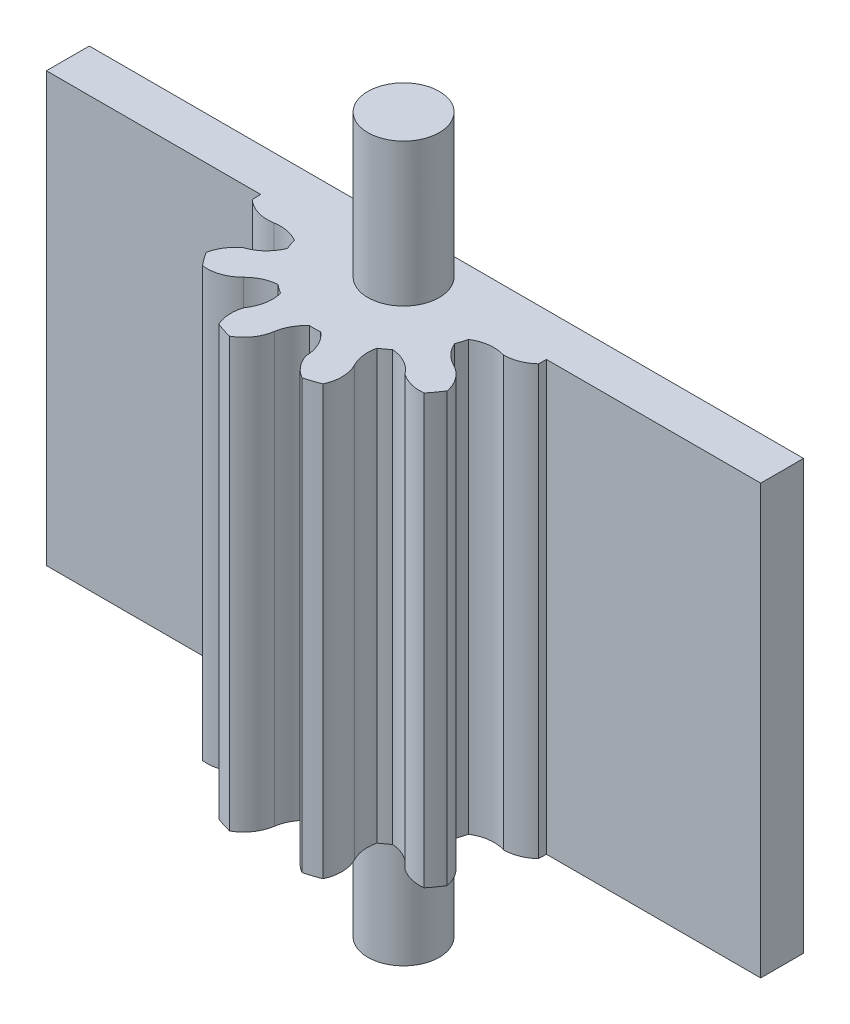
SolidWorks part; units mm, degrees
ref_plane "Alzado" through (0, 0, 0) normal (0, 0, 1) x (1, 0, 0)
ref_plane "Planta" through (0, 0, 0) normal (0, 1, 0) x (1, 0, 0)
ref_plane "Vista lateral" through (0, 0, 0) normal (1, 0, 0) x (0, 0, -1)
sketch "Croquis1" plane through (0, 0, 0) normal (0, 0, 1) x (1, 0, 0)
  line L1 (0, 0) -> (50, 0)
  line L2 (0, 0) -> (0, 30)
  line L3 (0, 30) -> (50, 30)
  line L4 (50, 0) -> (50, 30)
  dimension "D1" = 50
  dimension "D2" = 30
extrude "Saliente-Extruir1" add sketch "Croquis1" along normal blind 3
ref_plane "Plano1" through (0, 15, 0) normal (0, 1, 0) x (1, 0, 0)
sketch "Croquis2" plane through (0, 15, 0) normal (0, 1, 0) x (1, 0, 0)
  line L0 (50, -3) -> (0, -3) construction
  line L1 (15, -3) -> (35, -3)
  arc A0 (15, -3) -> (35, -3) centre (25, -3) ccw
  point P19 (0, 0)
  dimension "D1" = 20
extrude "Saliente-Extruir2" add sketch "Croquis2" along normal up to vertex (15 mm away) and the other way up to vertex (15 mm away)
sketch "Croquis3" plane through (0, 30, 0) normal (0, 1, 0) x (1, 0, 0)
  line L0 (25, -3) -> (18.9587, -4.6019) construction
  line L2 (25, -3) -> (21.0541, -7.847) construction
  arc A0 (17.281, -9.3575) -> (19.4133, -8.6169) centre (17.5958, -6.8239) ccw
  arc A2 (21.0541, -7.847) -> (19.4133, -8.6169) centre (21.2771, -10.4555) ccw
  arc A3 (21.0541, -7.847) -> (21.6882, -8.3005) centre (25, -3) ccw
  arc A6 (17.6058, -6.8433) -> (19.2052, -5.3416) centre (16.7783, -4.3595) ccw
  arc A8 (17.6058, -6.8433) -> (16.5983, -8.4232) centre (19.1632, -8.9478) ccw
  arc A9 (21.2771, -10.4555) -> (21.6882, -8.3005) centre (19.1476, -8.9325) ccw
  arc A10 (21.2771, -10.4555) -> (21.3905, -12.3259) centre (23.774, -11.2427) ccw
  arc A11 (18.9587, -4.6019) -> (17.1787, -4.2604) centre (17.6058, -6.8433) ccw
  arc A12 (18.9587, -4.6019) -> (19.2052, -5.3416) centre (25, -3) ccw
  arc A13 (15.0184, -3.6062) -> (17.1787, -4.2604) centre (16.7622, -1.7415) ccw
  arc A14 (16.5983, -8.4232) -> (15.0184, -3.6062) centre (25, -3) cw
  arc A15 (21.3905, -12.3259) -> (17.281, -9.3575) centre (25, -3) cw
  arc A16 (22.4921, -12.6804) -> (23.7818, -10.8279) centre (21.2575, -10.4457) ccw
  arc A17 (24.6567, -9.2406) -> (23.7818, -10.8279) centre (26.3703, -11.2199) ccw
  arc A18 (24.6567, -9.2406) -> (25.4363, -9.2348) centre (25, -3) ccw
  arc A19 (26.3703, -11.2199) -> (25.4363, -9.2348) centre (23.7523, -11.2394) ccw
  arc A20 (26.3703, -11.2199) -> (27.5615, -12.6664) centre (28.853, -10.3891) ccw
  arc A21 (27.5615, -12.6664) -> (22.4921, -12.6804) centre (25, -3) cw
  arc A22 (28.661, -12.3057) -> (28.6156, -10.049) centre (26.3487, -11.2235) ccw
  arc A23 (28.3904, -8.2506) -> (28.6156, -10.049) centre (30.9401, -8.8446) ccw
  arc A24 (28.3904, -8.2506) -> (29.0177, -7.7876) centre (25, -3) ccw
  arc A25 (30.9401, -8.8446) -> (29.0177, -7.7876) centre (28.8336, -10.3992) ccw
  arc A26 (30.9401, -8.8446) -> (32.754, -9.3147) centre (32.4604, -6.7132) ccw
  arc A27 (32.754, -9.3147) -> (28.661, -12.3057) centre (25, -3) cw
  arc A28 (33.4316, -8.3766) -> (32.0684, -6.5776) centre (30.9248, -8.8602) ccw
  arc A29 (30.8291, -5.255) -> (32.0684, -6.5776) centre (33.2411, -4.2369) ccw
  arc A30 (30.8291, -5.255) -> (31.0645, -4.5117) centre (25, -3) ccw
  arc A31 (33.2411, -4.2369) -> (31.0645, -4.5117) centre (32.4506, -6.7327) ccw
  arc A32 (33.2411, -4.2369) -> (34.9848, -3.551) centre (33.2181, -1.6189) ccw
  arc A33 (34.9848, -3.551) -> (33.4316, -8.3766) centre (25, -3) cw
  dimension "D1" = 5
  dimension "D3" = 5.2361
  dimension "D2" = 36
  dimension "D4" = 6.25
extrude "Cortar-Extruir1" cut sketch "Croquis3" against normal through all
sketch "Croquis4" plane through (0, 30, 0) normal (0, 1, 0) x (1, 0, 0)
  circle A0 centre (25, -3) radius 2.5
  arc A1 (15, -3) -> (34.9954, -2.6959) centre (25, -3) ccw construction
  arc A2 (34.9848, -3.551) -> (35, -3) centre (25, -3) ccw construction
  arc A3 (21.3905, -12.3259) -> (22.4921, -12.6804) centre (25, -3) ccw construction
  point P12 (0, 0)
  dimension "D1" = 5
extrude "Saliente-Extruir3" add sketch "Croquis4" along normal blind 10
mirror "Simetría2" about plane through (0, 15, 0) normal (0, 1, 0) of "Saliente-Extruir3"
